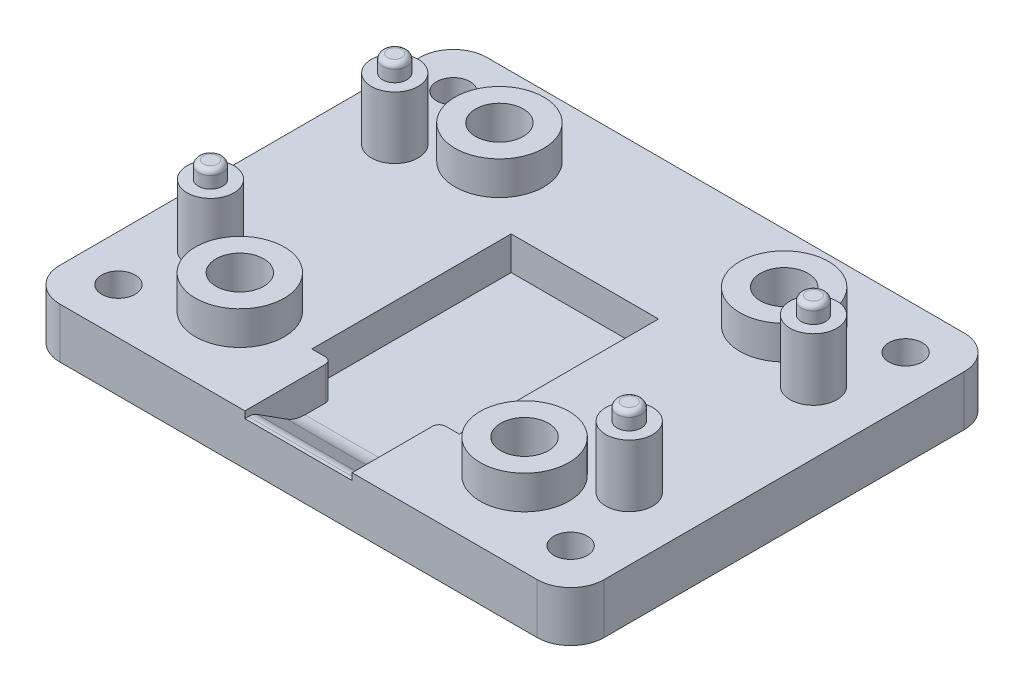
SolidWorks part; units mm, degrees
material "尼龙 101"
ref_plane "前视基准面" through (0, 0, 0) normal (0, 0, 1) x (1, 0, 0)
ref_plane "上视基准面" through (0, 0, 0) normal (0, 1, 0) x (1, 0, 0)
ref_plane "右视基准面" through (0, 0, 0) normal (1, 0, 0) x (0, 0, -1)
other "Configuration Table"
sketch "草图1" plane through (0, 0, 0) normal (0, 1, 0) x (1, 0, 0)
  line L1 (-16.25, 12.75) -> (16.25, 12.75)
  line L2 (-16.25, 12.75) -> (-16.25, -12.75)
  line L3 (-16.25, -12.75) -> (16.25, -12.75)
  line L4 (16.25, 12.75) -> (16.25, -12.75)
  line L5 (-16.25, 12.75) -> (16.25, -12.75) construction
  line L6 (-16.25, -12.75) -> (16.25, 12.75) construction
  point P0 (0, 0)
  dimension "D1" = 32.5
  dimension "D2" = 25.5
extrude "凸台-拉伸1" add sketch "草图1" along normal blind 3
sketch "草图2" plane through (0, 3, 0) normal (0, 1, 0) x (1, 0, 0)
  line L0 (0, 0) -> (0, 5.35) construction
  line L1 (-5.4, 5.35) -> (5.4, 5.35)
  line L2 (5.4, 5.35) -> (5.4, -7.55)
  line L3 (5.4, -7.55) -> (4.4, -7.55)
  line L4 (4.4, -7.55) -> (4.4, 4.35)
  line L5 (4.4, 4.35) -> (-4.4, 4.35)
  line L6 (-4.4, -7.55) -> (-4.4, 4.35)
  line L7 (-5.4, -7.55) -> (-4.4, -7.55)
  line L8 (-5.4, 5.35) -> (-5.4, -7.55)
  point P9 (0, 4.35)
  dimension "D1" = 8.8
  dimension "D2" = 11.9
  dimension "D3" = 4.35
  dimension "D4" = 1
  dimension "D5" = 1
extrude "凸台-拉伸2" add sketch "草图2" along normal blind 1.5
sketch "草图5" plane through (0, 3, 0) normal (0, 1, 0) x (1, 0, 0)
  line L0 (0, 12.75) -> (0, 0) construction
  line L1 (16.25, 12.75) -> (-16.25, 12.75) construction
  line L2 (0, 0) -> (16.25, 0) construction
  line L3 (16.25, -12.75) -> (16.25, 12.75) construction
  circle A0 centre (12.5, 5.5) radius 1.4
  circle A1 centre (12.5, -5.5) radius 1.4
  circle A2 centre (-12.5, -5.5) radius 1.4
  circle A3 centre (-12.5, 5.5) radius 1.4
  dimension "D1" = 2.8
  dimension "D2" = 25
  dimension "D3" = 11
extrude "凸台-拉伸3" add sketch "草图5" along normal blind 3.7
sketch "草图6" plane through (0, 6.7, 0) normal (0, 1, 0) x (1, 0, 0)
  circle A0 centre (-12.5, -5.5) radius 0.725
  circle A1 centre (-12.5, 5.5) radius 0.725
  circle A2 centre (12.5, 5.5) radius 0.725
  circle A3 centre (12.5, -5.5) radius 0.725
  dimension "D1" = 1.45
extrude "凸台-拉伸4" add sketch "草图6" along normal blind 1
sketch "草图7" plane through (0, 3, 0) normal (0, 1, 0) x (1, 0, 0)
  line L0 (0, 0) -> (0, 12.75) construction
  line L1 (16.25, 12.75) -> (-16.25, 12.75) construction
  line L2 (0, 0) -> (16.25, 0) construction
  line L3 (16.25, -12.75) -> (16.25, 12.75) construction
  circle A0 centre (13.5, 10) radius 1
  circle A1 centre (-13.5, 10) radius 1
  circle A2 centre (-13.5, -10) radius 1
  circle A3 centre (13.5, -10) radius 1
  dimension "D1" = 2
  dimension "D2" = 20
  dimension "D3" = 27
extrude "切除-拉伸1" cut sketch "草图7" against normal blind 10
sketch "草图8" plane through (0, 0, 0) normal (0, -1, 0) x (1, 0, 0)
  circle A0 centre (-13.5, 10) radius 2
  circle A1 centre (13.5, 10) radius 2
  circle A2 centre (13.5, -10) radius 2
  circle A3 centre (-13.5, -10) radius 2
  dimension "D1" = 4
extrude "切除-拉伸2" cut sketch "草图8" against normal blind 1
fillet "圆角1" radius 2 4 edges at (-16.25, 1.5, -12.75) (16.25, 1.5, -12.75) (-16.25, 1.5, 12.75) (16.25, 1.5, 12.75)
sketch "草图9" plane through (0, 3, 0) normal (0, 1, 0) x (1, 0, 0)
  line L0 (0, 12.75) -> (0, 0) construction
  line L1 (14.25, 12.75) -> (-14.25, 12.75) construction
  line L2 (0, 0) -> (16.25, 0) construction
  line L3 (16.25, -10.75) -> (16.25, 10.75) construction
  circle A0 centre (8.5, 7.75) radius 2.65
  circle A1 centre (-8.5, 7.75) radius 2.65
  circle A2 centre (-8.5, -7.75) radius 2.65
  circle A3 centre (8.5, -7.75) radius 2.65
  dimension "D1" = 17
  dimension "D2" = 15.5
  dimension "D3" = 5.3
extrude "凸台-拉伸5" add sketch "草图9" along normal blind 2
sketch "草图11" plane through (0, 5, 0) normal (0, 1, 0) x (1, 0, 0)
  circle A0 centre (-8.5, 7.75) radius 1.05
  circle A1 centre (-8.5, -7.75) radius 1.05
  circle A2 centre (8.5, -7.75) radius 1.05
  circle A3 centre (8.5, 7.75) radius 1.05
  dimension "D1" = 2.1
extrude "切除-拉伸4" cut sketch "草图11" against normal blind 100
sketch "草图12" plane through (0, 5, 0) normal (0, 1, 0) x (1, 0, 0)
  circle A0 centre (-8.5, 7.75) radius 1.425
  circle A1 centre (8.5, 7.75) radius 1.425
  circle A2 centre (-8.5, -7.75) radius 1.425
  circle A3 centre (8.5, -7.75) radius 1.425
  dimension "D1" = 2.85
extrude "切除-拉伸5" cut sketch "草图12" against normal blind 4
fillet "圆角2" radius 0.3 4 edges at (12.5, 7.7, -4.775) (12.5, 7.7, 6.225) (-12.5, 7.7, 6.225) (-12.5, 7.7, -4.775)
sketch "草图15" plane through (0, 3, 0) normal (0, 1, 0) x (1, 0, 0)
  line L0 (0, 0) -> (0, 12.75) construction
  line L1 (14.25, 12.75) -> (-14.25, 12.75) construction
  line L2 (-4.4, 4.35) -> (4.4, 4.35)
  line L3 (4.4, 4.35) -> (4.4, -7.55)
  line L4 (4.4, -7.55) -> (3.2, -7.55)
  line L5 (3.2, -7.55) -> (3.2, -12.75)
  line L6 (-14.25, -12.75) -> (14.25, -12.75) construction
  line L7 (3.2, -12.75) -> (-3.2, -12.75)
  line L8 (-3.2, -7.55) -> (-3.2, -12.75)
  line L9 (-4.4, -7.55) -> (-3.2, -7.55)
  line L10 (-4.4, 4.35) -> (-4.4, -7.55)
  line L11 (4.4, 4.35) -> (4.4, -7.55) construction
  point P14 (0, -12.75)
  point P17 (0, 4.35)
  dimension "D1" = 6.4
extrude "切除-拉伸8" cut sketch "草图15" against normal blind 2
sketch "草图17" plane through (0, 4.5, 0) normal (0, 1, 0) x (1, 0, 0)
  line L8 (-4.4, -7.55) -> (-4.4, 4.35)
  line L9 (-4.4, 4.35) -> (4.4, 4.35)
  line L10 (4.4, 4.35) -> (4.4, -7.55)
  line L11 (4.4, -7.55) -> (5.4, -7.55)
  line L12 (5.4, -7.55) -> (5.4, 5.35)
  line L13 (5.4, 5.35) -> (-5.4, 5.35)
  line L14 (-5.4, 5.35) -> (-5.4, -7.55)
  line L15 (-5.4, -7.55) -> (-4.4, -7.55)
  line L16 (-4.4, -7.55) -> (-4.4, 4.35)
  line L17 (-4.4, 4.35) -> (4.4, 4.35)
  line L18 (4.4, 4.35) -> (4.4, -7.55)
  line L19 (4.4, -7.55) -> (5.4, -7.55)
  line L20 (5.4, -7.55) -> (5.4, 5.35)
  line L21 (5.4, 5.35) -> (-5.4, 5.35)
  line L22 (-5.4, 5.35) -> (-5.4, -7.55)
  line L23 (-5.4, -7.55) -> (-4.4, -7.55)
  dimension "D1" = 0
extrude "切除-拉伸9" cut sketch "草图17" against normal blind 1.5
sketch "草图18" plane through (3.2, 0, 0) normal (-1, 0, 0) x (0, 0, 1)
  line L0 (12.75, 1) -> (9.75, 1)
  line L2 (12.75, 1) -> (12.75, 3) construction
  line L3 (12.75, 2.6) -> (12.75, 1)
  line L5 (12.75, 3) -> (12.75, 0) construction
  line L6 (12.75, 2.6) -> (12.25, 2.6)
  line L7 (12.25, 2.6) -> (9.75, 1)
  line L8 (12.75, 3) -> (10.75, 3) construction
  dimension "D1" = 3
  dimension "D2" = 0.4
  dimension "D3" = 0.5
extrude "凸台-拉伸6" add sketch "草图18" along normal up to surface (6.4 mm away) up to face at (-3.2, 2, 10.15)
fillet "圆角3" radius 2 1 edges at (0, 1, 9.75)
fillet "圆角5" radius 1 1 edges at (0, 2.6, 12.25)
fillet "圆角6" radius 0.4 2 edges at (3.2, 2, 7.55) (-3.2, 2, 7.55)
